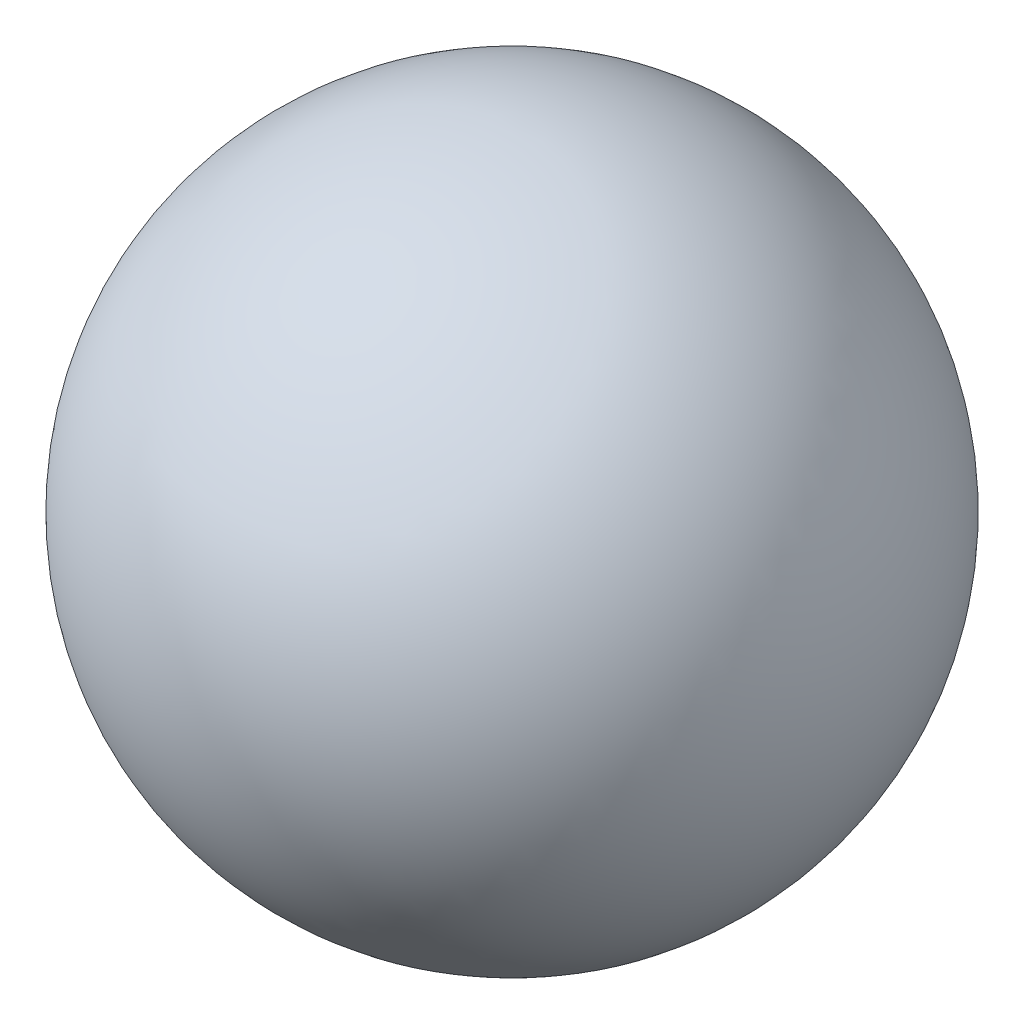
SolidWorks part; units mm, degrees
material "BUTYL"
ref_plane "Front Plane" through (0, 0, 0) normal (0, 0, 1) x (1, 0, 0)
ref_plane "Top Plane" through (0, 0, 0) normal (0, 1, 0) x (1, 0, 0)
ref_plane "Right Plane" through (0, 0, 0) normal (1, 0, 0) x (0, 0, -1)
sketch "Sketch1" plane through (0, 0, 0) normal (0, 0, 1) x (1, 0, 0)
  line L0 (0, 24.5) -> (0, -24.5)
  arc A0 (0, 24.5) -> (0, -24.5) centre (0, 0) ccw
  dimension "D1" = 49
revolve "Revolve1" add sketch "Sketch1" angle 360 about L0
sketch "Sketch2" plane through (0, 0, 0) normal (0, 0, 1) x (1, 0, 0)
  circle A0 centre (0, 0) radius 24.5 construction
  point P0 (0, 24.5)
  point P1 (-24.5, 0)
  point P4 (24.5, 0)
  point P5 (0, -24.5)
  point P6 (0, 0)
sketch "Sketch4" plane through (0, 0, 0) normal (0, 0, 1) x (1, 0, 0)
  line L0 (-24.5, 0) -> (24.5, 0) construction
  line L1 (0, 24.5) -> (0, -24.5) construction
sketch "Sketch5" plane through (0, 0, 0) normal (1, 0, 0) x (0, 0, -1)
  line L0 (-24.5, 0) -> (24.5, 0) construction
  circle A0 centre (0, 0) radius 24.5 construction
  point P0 (-24.5, 0)
  point P1 (24.5, 0)
